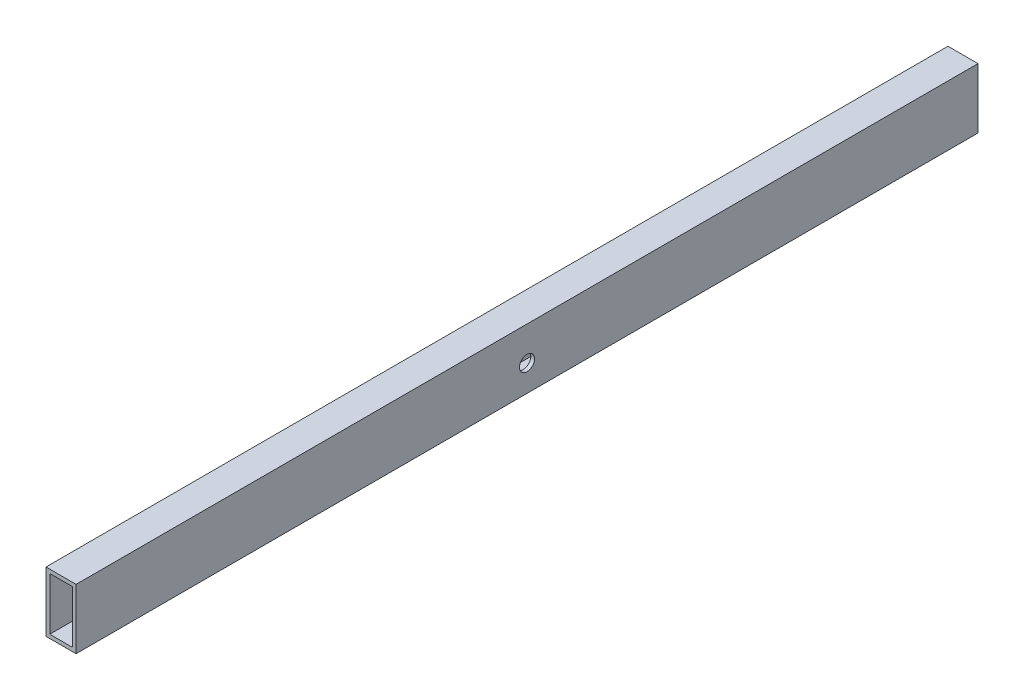
SolidWorks part; units mm, degrees
ref_plane "Front Plane" through (0, 0, 0) normal (0, 0, 1) x (1, 0, 0)
ref_plane "Top Plane" through (0, 0, 0) normal (0, 1, 0) x (1, 0, 0)
ref_plane "Right Plane" through (0, 0, 0) normal (1, 0, 0) x (0, 0, -1)
sketch "Sketch1" plane through (0, 0, 0) normal (0, 0, 1) x (1, 0, 0)
  line L0 (-7.6235, 14.5253) -> (11.4265, 14.5253)
  line L1 (-10.7985, 17.7003) -> (14.6015, 17.7003)
  line L2 (-10.7985, 17.7003) -> (-10.7985, -33.0997)
  line L3 (-10.7985, -33.0997) -> (14.6015, -33.0997)
  line L4 (14.6015, 17.7003) -> (14.6015, -33.0997)
  line L5 (11.4265, 14.5253) -> (11.4265, -29.9247)
  line L6 (-7.6235, -29.9247) -> (11.4265, -29.9247)
  line L7 (-7.6235, 14.5253) -> (-7.6235, -29.9247)
  dimension "D1" = 25.4
  dimension "D2" = 50.8
  dimension "D3" = 3.175
extrude "Boss-Extrude1" add sketch "Sketch1" along normal mid plane 762
sketch "Sketch2" plane through (14.6015, 0, 0) normal (1, 0, 0) x (0, 0, -1)
  line L1 (-381, -33.0997) -> (381, -33.0997) construction
  circle A0 centre (0, -10.8747) radius 6.35
  point P2 (0, 17.7003)
  dimension "D2" = 22.225
extrude "Cut-Extrude1" cut sketch "Sketch2" against normal blind 25.4
